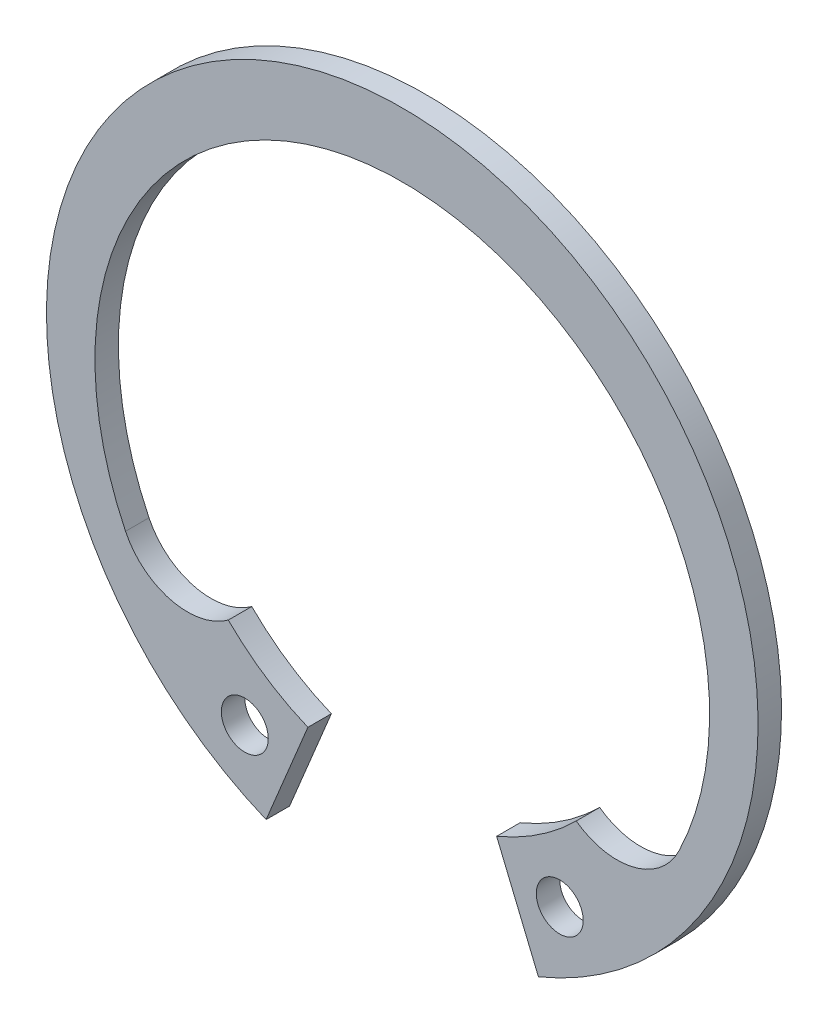
SolidWorks part; units mm, degrees
ref_plane "Front" through (0, 0, 0) normal (0, 0, 1) x (1, 0, 0)
ref_plane "Top" through (0, 0, 0) normal (0, 1, 0) x (1, 0, 0)
ref_plane "Right" through (0, 0, 0) normal (1, 0, 0) x (0, 0, -1)
sketch "Sketch1" plane through (0, 0, 0) normal (0, 0, 1) x (1, 0, 0)
  line L0 (-6.0349, -14.5696) -> (-8.706, -21.0183)
  line L1 (6.0349, -14.5696) -> (8.706, -21.0183)
  line L2 (0, 17.9027) -> (0, -23.5886) construction
  arc A0 (8.706, -21.0183) -> (-8.706, -21.0183) centre (0, 0) ccw
  arc A1 (17.6936, -9.5474) -> (-17.6936, -9.5474) centre (0, -1) ccw
  arc A2 (7.3858, -17.8309) -> (-7.3858, -17.8309) centre (0, 0) ccw construction
  circle A3 centre (10.0677, -16.4661) radius 1.5
  arc A4 (-17.6936, -9.5474) -> (-11.1243, -11.1778) centre (-13.7317, -7.6335) ccw
  arc A5 (-11.1243, -11.1778) -> (-6.0349, -14.5696) centre (0, 0) ccw
  circle A6 centre (-10.0677, -16.4661) radius 1.5
  arc A8 (11.1243, -11.1778) -> (6.0349, -14.5696) centre (0, 0) cw
  arc A9 (17.6936, -9.5474) -> (11.1243, -11.1778) centre (13.7317, -7.6335) cw
  dimension "R2" = 4.4
  dimension "d1" = 3
  dimension "d0" = 39.3
  dimension "D" = 45.5
  dimension "R" = 19.3
  dimension "a" = 6.98
  dimension "c" = 1
  dimension "Angle" = 45
  dimension "B" = 6
  dimension "B1" = 3
extrude "Body" add sketch "Sketch1" against normal blind 1.5
